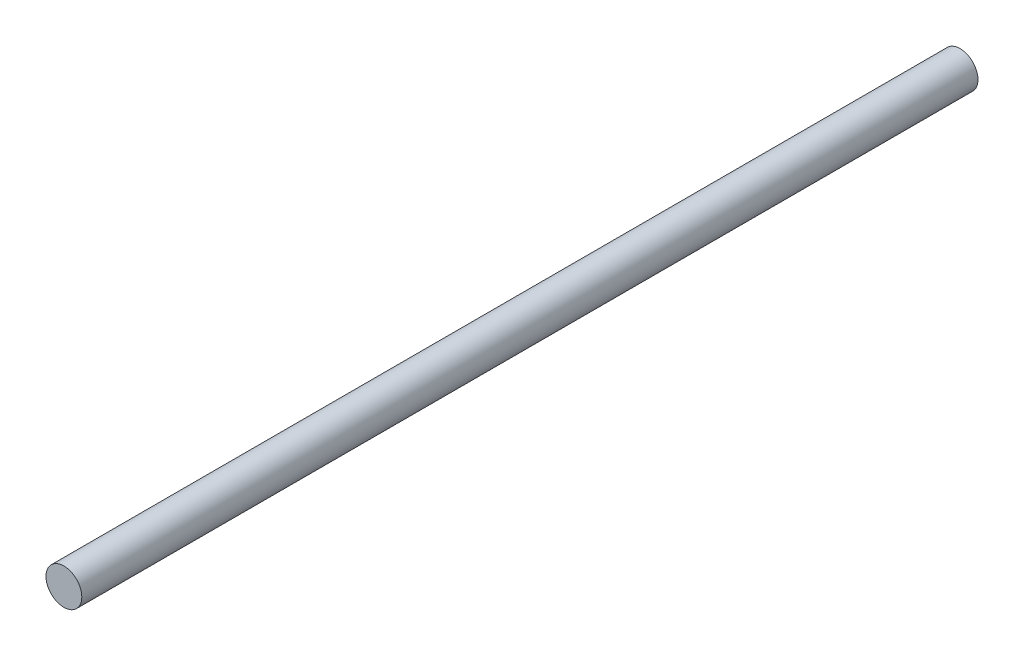
SolidWorks part; units mm, degrees
material "AISI 304"
ref_plane "前视基准面" through (0, 0, 0) normal (0, 0, 1) x (1, 0, 0)
ref_plane "上视基准面" through (0, 0, 0) normal (0, 1, 0) x (1, 0, 0)
ref_plane "右视基准面" through (0, 0, 0) normal (1, 0, 0) x (0, 0, -1)
sketch "草图1" plane through (0, 0, 0) normal (0, 0, 1) x (1, 0, 0)
  circle A0 centre (0, 0) radius 0.5
  dimension "D1" = 1
extrude "凸台-拉伸1" add sketch "草图1" along normal blind 25
